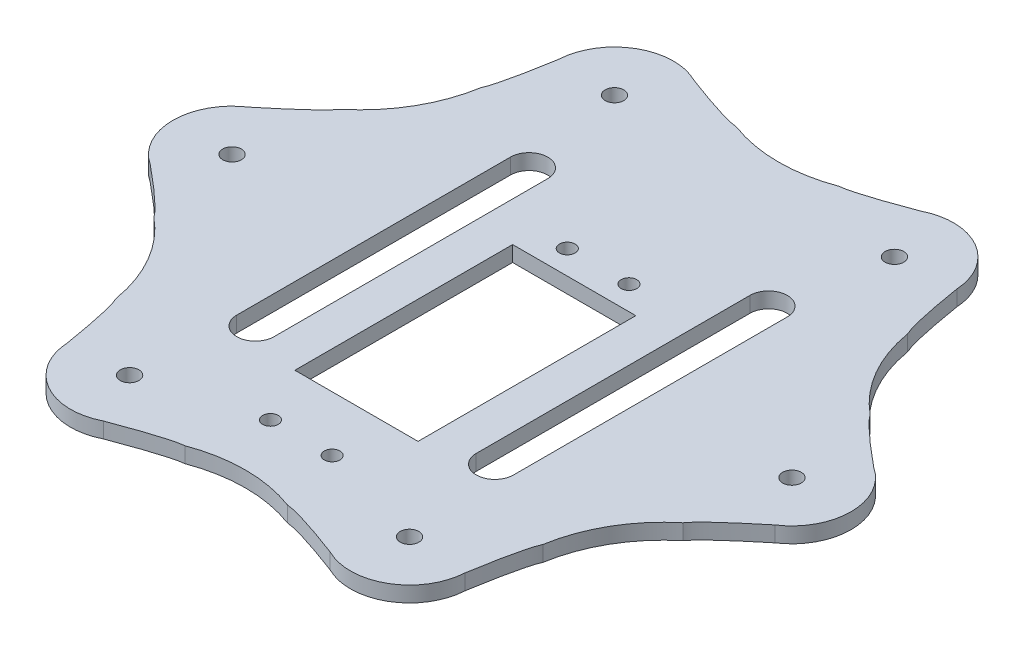
SolidWorks part; units mm, degrees
material "ABS"
ref_plane "Front" through (0, 0, 0) normal (0, 0, 1) x (1, 0, 0)
ref_plane "Top" through (0, 0, 0) normal (0, 1, 0) x (1, 0, 0)
ref_plane "Right" through (0, 0, 0) normal (1, 0, 0) x (0, 0, -1)
sketch "Sketch1" plane through (0, 0, 0) normal (0, 1, 0) x (1, 0, 0)
  line L0 (0, 45) -> (0, -45) construction
  line L1 (-45, 0) -> (45, 0) construction
  line L2 (-9.9, -25) -> (-9.9, 0)
  line L3 (9.9, -25) -> (9.9, 0)
  line L4 (-9.9, 0) -> (-9.9, 10)
  line L5 (-9.9, -25) -> (9.9, -25)
  line L6 (-22.25, 22) -> (-22.25, -22)
  line L7 (-16.25, 22) -> (-16.25, -22)
  line L8 (16.25, 22) -> (16.25, -22)
  line L9 (22.25, 22) -> (22.25, -22)
  line L10 (0, 45) -> (0, 37.5) construction
  line L11 (9.9, 0) -> (9.9, 10)
  line L12 (-9.9, 10) -> (9.9, 10)
  line L16 (-4.955, 13.84) -> (-4.955, -33.87) construction
  line L18 (0, 6.1303) -> (0, -27.7397) construction
  circle A0 centre (0, 0) radius 45
  arc A1 (-22.25, 22) -> (-16.25, 22) centre (-19.25, 22) cw
  arc A2 (-22.25, -22) -> (-16.25, -22) centre (-19.25, -22) ccw
  arc A3 (22.25, -22) -> (16.25, -22) centre (19.25, -22) cw
  arc A4 (22.25, 22) -> (16.25, 22) centre (19.25, 22) ccw
  circle A5 centre (-4.955, -33.87) radius 1.2573
  circle A6 centre (4.955, -33.87) radius 1.2573
  circle A7 centre (-4.955, 13.84) radius 1.2573
  circle A8 centre (4.955, 13.84) radius 1.2573
  point P11 (0, 24.3484)
  point P13 (9.9, 0)
  point P14 (-9.9, 0)
  point P18 (-22.25, 0)
  point P28 (22.25, 0)
  point P30 (0, 0)
  point P40 (0, 0)
  point P41 (0, 0)
  dimension "D3" = 3
  dimension "D5" = 9.91
  dimension "D6" = 90
  dimension "D7" = 19.8
  dimension "D9" = 9.91
  dimension "D10" = 2.5146
  dimension "D1" = 25
  dimension "D2" = 10
  dimension "D4" = 47.71
  dimension "D8" = 33.87
  dimension "D11" = 19.25
  dimension "D12" = 24.3484
extrude "Boss-Extrude2" add sketch "Sketch1" along normal blind 2.5
ref_plane "Plane1" through (0, 2.5, 0) normal (0, 1, 0) x (1, 0, 0)
sketch "Sketch2" plane through (0, 2.5, 0) normal (0, 1, 0) x (1, 0, 0)
  line L0 (0, 45) -> (0, -45) construction
  line L1 (-45, 0) -> (45, 0) construction
  line L2 (-54.5, 0) -> (-35.5, 0) construction
  line L4 (-51.7175, -6.7175) -> (-45, 0) construction
  circle A0 centre (0, 0) radius 45 construction
  arc A2 (-42.2345, 15.532) -> (-42.2345, -15.532) centre (0, 0) ccw
  arc A3 (-50.2124, 7.9424) -> (-50.2124, -7.9424) centre (-45, 0) ccw
  spline S0 degree 3 poles (-50.2124, -7.9424) (-45.316, -11.9596) (-42.6567, -14.4895) (-42.2345, -15.532) knots 0.089312 0.089312 0.089312 0.089312 1 1 1 1
  spline S1 degree 3 poles (-50.2124, 7.9424) (-45.316, 11.9596) (-42.6567, 14.4895) (-42.2345, 15.532) knots 0.089312 0.089312 0.089312 0.089312 1 1 1 1
  dimension "D2" = 45
extrude "Boss-Extrude4" add sketch "Sketch2" against normal up to surface (2.5 mm away) up to face at (-19.25, 0, 0)
pattern_circular "CirPattern1" count 6 over 360 about axis through (0, 2.5, 0) along (0, 1, 0) of "Boss-Extrude4"
ref_plane "Plane2" through (0, 2.5, 0) normal (0, 1, 0) x (1, 0, 0)
sketch "Sketch5" plane through (0, 2.5, 0) normal (0, 1, 0) x (1, 0, 0)
  line L0 (0, 45) -> (0, -45) construction
  line L1 (-8.2247, 44.3422) -> (0, 46.6578)
  line L2 (0, 46.6578) -> (8.2247, 44.3422)
  line L3 (40.4069, 23.3289) -> (42.5138, 15.0483)
  line L4 (34.2891, 29.2939) -> (40.4069, 23.3289)
  line L5 (40.4069, -23.3289) -> (34.2891, -29.2939)
  line L6 (42.5138, -15.0483) -> (40.4069, -23.3289)
  line L7 (0, -46.6578) -> (-8.2247, -44.3422)
  line L8 (8.2247, -44.3422) -> (0, -46.6578)
  line L9 (-40.4069, -23.3289) -> (-42.5138, -15.0483)
  line L10 (-34.2891, -29.2939) -> (-40.4069, -23.3289)
  line L11 (-40.4069, 23.3289) -> (-34.2891, 29.2939)
  line L12 (-42.5138, 15.0483) -> (-40.4069, 23.3289)
  arc A0 (7.6662, 44.3422) -> (-7.6662, 44.3422) centre (0, 0) ccw construction
  arc A1 (-7.6662, -44.3422) -> (7.6662, -44.3422) centre (0, 0) ccw construction
  arc A2 (-8.2247, 44.3422) -> (8.2247, 44.3422) centre (0, 66.2885) ccw
  arc A3 (34.2891, 29.2939) -> (42.5138, 15.0483) centre (57.4076, 33.1443) ccw
  arc A4 (42.5138, -15.0483) -> (34.2891, -29.2939) centre (57.4076, -33.1443) ccw
  arc A5 (8.2247, -44.3422) -> (-8.2247, -44.3422) centre (0, -66.2885) ccw
  arc A6 (-34.2891, -29.2939) -> (-42.5138, -15.0483) centre (-57.4076, -33.1443) ccw
  arc A7 (-42.5138, 15.0483) -> (-34.2891, 29.2939) centre (-57.4076, 33.1443) ccw
  parabola Q0 (-7.6662, 44.3422) -> (-18.2279, 47.4564) focus (-7.4049, 44.5798) apex (-7.3043, 44.5299) construction
  parabola Q1 (18.2279, 47.4564) -> (7.6662, 44.3422) focus (7.4049, 44.5798) apex (7.3043, 44.5299) construction
  point P42 (0, 0)
  dimension "D1" = 6
extrude "Cut-Extrude2" cut sketch "Sketch5" against normal blind 2.5
ref_plane "Plane3" through (0, 2.5, 0) normal (0, 1, 0) x (1, 0, 0)
sketch "Sketch6" plane through (0, 2.5, 0) normal (0, 1, 0) x (1, 0, 0)
  line L0 (0, 42.8517) -> (0, -42.8517) construction
  circle A0 centre (-45, 0) radius 1.5
  arc A1 (-8.2247, 44.3422) -> (8.2247, 44.3422) centre (0, 66.2885) ccw construction
  arc A2 (8.2247, -44.3422) -> (-8.2247, -44.3422) centre (0, -66.2885) ccw construction
  circle A7 centre (-22.5, 38.9711) radius 1.5
  circle A8 centre (22.5, 38.9711) radius 1.5
  circle A9 centre (45, 0) radius 1.5
  circle A10 centre (22.5, -38.9711) radius 1.5
  circle A11 centre (-22.5, -38.9711) radius 1.5
  point P37 (0, 0)
  dimension "D4" = 3
  dimension "D5" = 22.5
  dimension "D3" = 6
extrude "Cut-Extrude3" cut sketch "Sketch6" against normal mid plane 10
